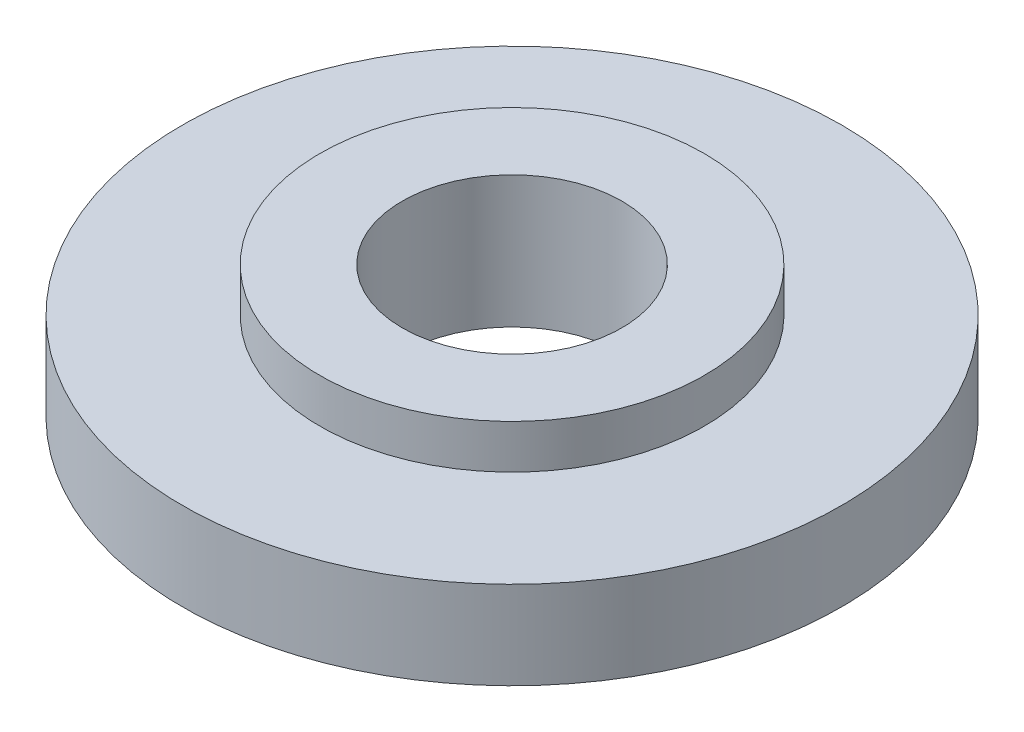
SolidWorks part; units mm, degrees
ref_plane "前视基准面" through (0, 0, 0) normal (0, 0, 1) x (1, 0, 0)
ref_plane "上视基准面" through (0, 0, 0) normal (0, 1, 0) x (1, 0, 0)
ref_plane "右视基准面" through (0, 0, 0) normal (1, 0, 0) x (0, 0, -1)
other "Configuration Table"
sketch "草图1" plane through (0, 0, 0) normal (0, 0, 1) x (1, 0, 0)
  line L0 (0, -10) -> (0, 30) construction
  line L1 (20, 0) -> (60, 0)
  line L2 (60, 0) -> (60, 16)
  line L3 (60, 16) -> (35, 16)
  line L4 (35, 16) -> (35, 24)
  line L5 (35, 24) -> (20, 24)
  line L6 (20, 24) -> (20, 0)
revolve "旋转1" add sketch "草图1" angle 360 about L0
sketch "草图2" plane through (0, 0, 0) normal (0, 1, 0) x (1, 0, 0)
  circle A0 centre (45, 0) radius 7
  circle A1 centre (22.5, 0) radius 7
  circle A2 centre (-22.5, 0) radius 7
  circle A3 centre (-45, 0) radius 7
  circle A4 centre (-22.5, 0) radius 7
  circle A5 centre (22.5, 0) radius 7
